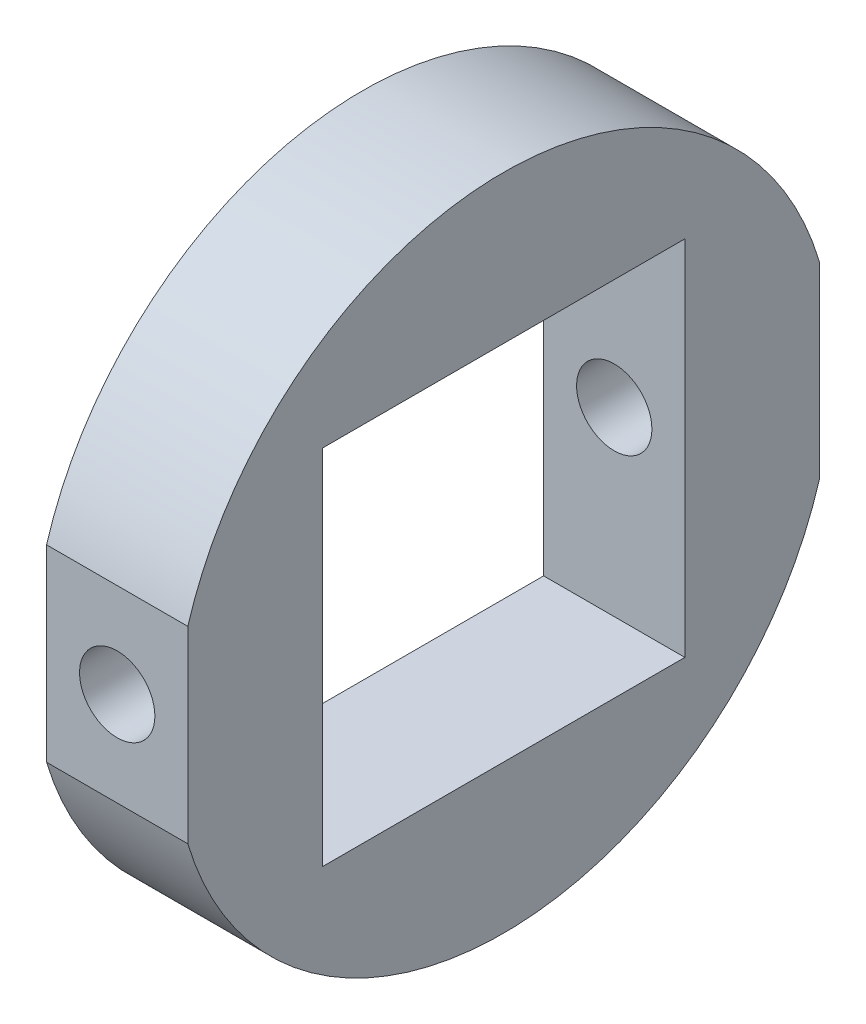
SolidWorks part; units mm, degrees
material "PLA"
ref_plane "前视基准面" through (0, 0, 0) normal (0, 0, 1) x (1, 0, 0)
ref_plane "上视基准面" through (0, 0, 0) normal (0, 1, 0) x (1, 0, 0)
ref_plane "右视基准面" through (0, 0, 0) normal (1, 0, 0) x (0, 0, -1)
sketch "草图1" plane through (0, 0, 0) normal (1, 0, 0) x (0, 0, -1)
  line L0 (13.4164, 4) -> (13.4164, -4)
  line L1 (-7.7, 7.7) -> (7.7, 7.7)
  line L2 (-7.7, 7.7) -> (-7.7, -7.7)
  line L3 (-7.7, -7.7) -> (7.7, -7.7)
  line L4 (7.7, 7.7) -> (7.7, -7.7)
  line L5 (-7.7, 7.7) -> (7.7, -7.7) construction
  line L6 (-7.7, -7.7) -> (7.7, 7.7) construction
  line L7 (0, 0) -> (13.4164, 0) construction
  line L8 (0, 17.6804) -> (0, -16.4662) construction
  line L9 (-13.4164, 4) -> (-13.4164, -4)
  arc A0 (-13.4164, -4) -> (13.4164, -4) centre (0, 0) ccw
  arc A1 (13.4164, 4) -> (-13.4164, 4) centre (0, 0) ccw
  point P0 (0, 0)
  dimension "D2" = 28
  dimension "D1" = 15.4
  dimension "D3" = 8
extrude "凸台-拉伸1" add sketch "草图1" along normal mid plane 6
sketch "草图3" plane through (0, 0, 13.4164) normal (0, 0, 1) x (1, 0, 0)
  circle A0 centre (0, 0) radius 1.6
  dimension "D1" = 3.2
extrude "切除-拉伸1" cut sketch "草图3" against normal through all
move or copy body "实体-移动/复制1" [suppressed] bodies to move or copy 107
